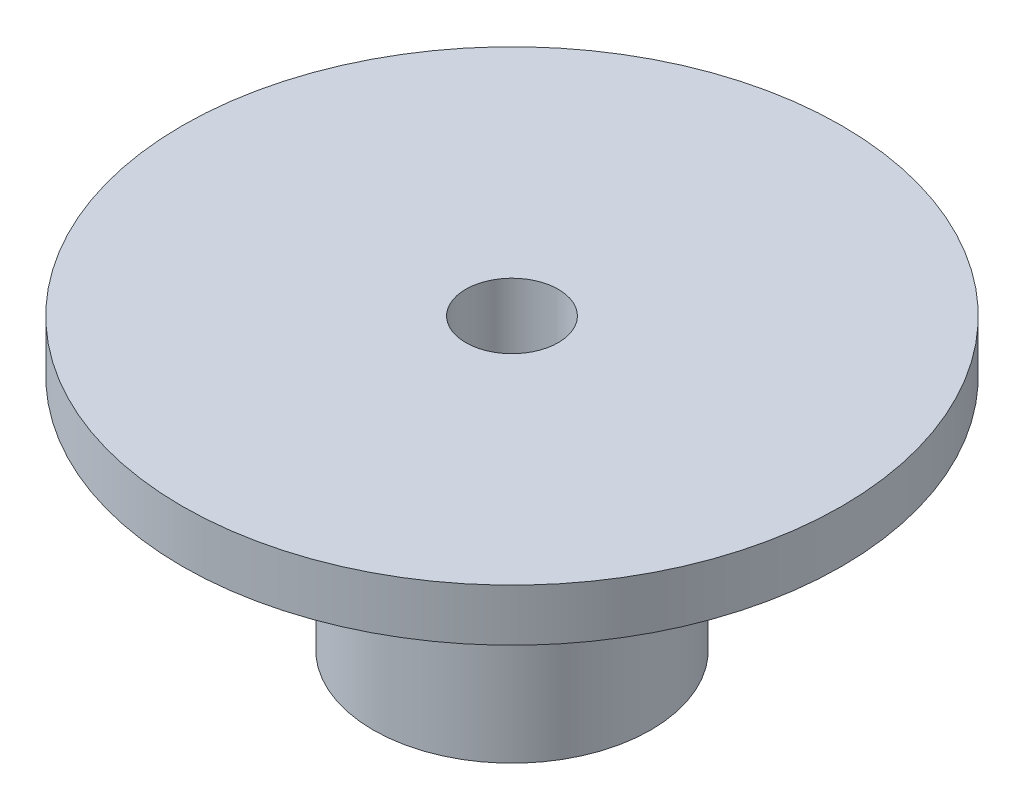
SolidWorks part; units mm, degrees
ref_plane "Front Plane" through (0, 0, 0) normal (0, 0, 1) x (1, 0, 0)
ref_plane "Top Plane" through (0, 0, 0) normal (0, 1, 0) x (1, 0, 0)
ref_plane "Right Plane" through (0, 0, 0) normal (1, 0, 0) x (0, 0, -1)
sketch "Sketch2" plane through (0, 0, 0) normal (0, 1, 0) x (1, 0, 0)
  circle A0 centre (0, 0) radius 28.5
  circle A1 centre (0, 0) radius 4
  dimension "D1" = 57
  dimension "D2" = 8
extrude "Boss-Extrude1" add sketch "Sketch2" along normal blind 25
sketch "Sketch4" plane through (0, 0, 0) normal (0, -1, 0) x (1, 0, 0)
  circle A0 centre (0, 0) radius 12
  dimension "D1" = 24
extrude "Cut-Extrude2" cut sketch "Sketch4" against normal blind 20.5 flip side to cut
